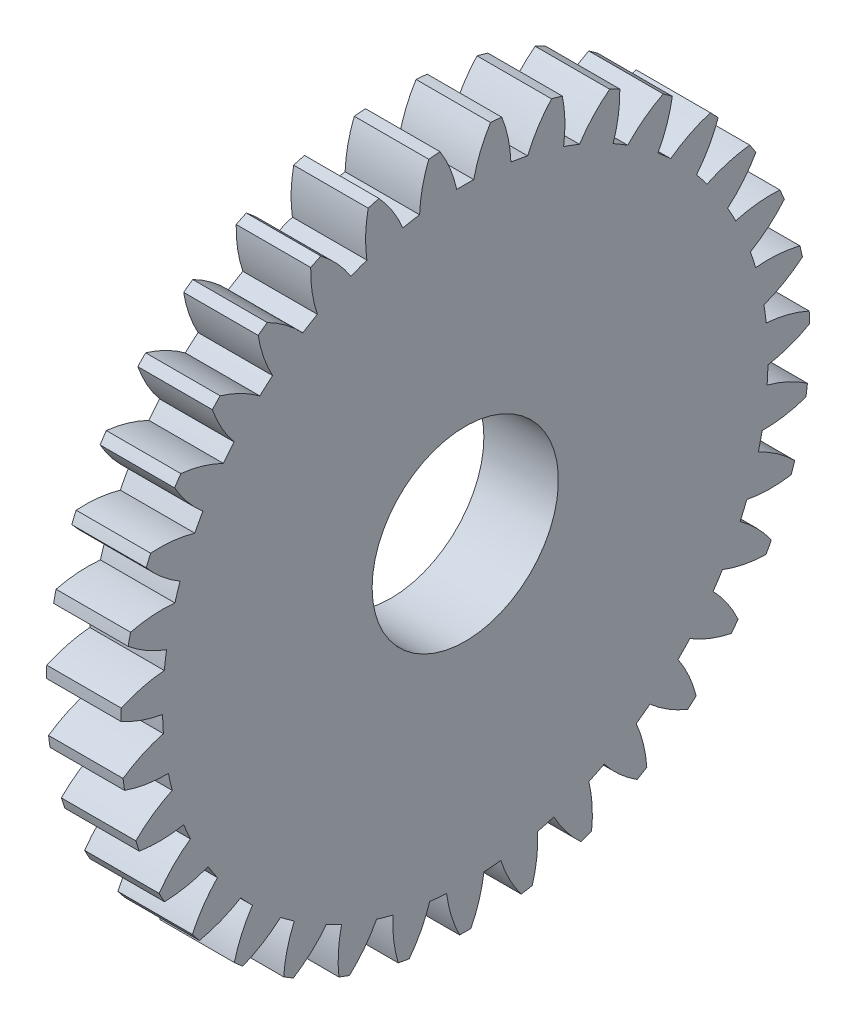
SolidWorks part; units mm, degrees
ref_plane "Plane1" through (0, 0, 0) normal (0, 0, 1) x (1, 0, 0)
ref_plane "Plane2" through (0, 0, 0) normal (0, 1, 0) x (1, 0, 0)
ref_plane "Plane3" through (0, 0, 0) normal (1, 0, 0) x (0, 0, -1)
sketch "HoldingSke" plane through (0, 0, 0) normal (0, 1, 0) x (1, 0, 0)
  line L0 (0, 0) -> (0.8192, -0.5736)
  line L1 (-15, 0) -> (100, 0) construction
  line L2 (0, 0) -> (-2.1039, 2.3779)
  line L3 (0, 0) -> (-11.863, 4.5341)
  line L4 (0, 0) -> (7.0742, 4.9534)
  line L5 (0, 0) -> (-46.8476, -17.4728)
  line L6 (0, 0) -> (-3.3159, -2.2372)
  line L7 (-2.1039, 2.3779) -> (8.6586, 51.2059)
  line L8 (-76.2, 54.61) -> (-74.4, 54.61)
  line L9 (-71.009, 38.7566) -> (-53.1078, 45.2721)
  line L10 (-76.2, 71.12) -> (104.1128, 71.12)
  line L11 (0, 0) -> (-4, 0)
  line L12 (-76.2, 101.6) -> (-76.162, 101.6)
  line L13 (24.9733, 27.94) -> (52.9518, 28.4284)
  line L14 (24.9733, 27.94) -> (24.9743, 27.94)
  line L15 (24.9733, 27.94) -> (100.4006, 29.5858)
  line L16 (-63.627, -1) -> (-12.827, -1)
  circle A0 centre (0, 0) radius 5
  circle A1 centre (0, 0) radius 16.249
  circle A2 centre (0, 0) radius 37.5
  circle A3 centre (0, 0) radius 5
  dimension "MHD" = 32.498
  dimension "Hub_dia" = 75
  dimension "Bore" = 10
  dimension "MBD" = 10
  dimension "Num_teeth" = 35
  dimension "Pitch" = 1
  dimension "Overall_len" = 50
  dimension "Show_teeth" = 35
  dimension "Thickness" = 4
  dimension "OAL" = 50.0001
  dimension "T_dim" = 1.8
  dimension "Ap" = 20
  dimension "H" = 19.05
  dimension "Pitch_radius" = 180.3128
  dimension "Width" = 4
  dimension "Backlash" = 0.038
  dimension "Addendum_fac" = 1
  dimension "Dedendum_fac" = 1.25
  dimension "Clearance_fac" = 0.25
  dimension "Dedendum_add" = 0.001
  dimension "Module" = 1
sketch "BasProSke" plane through (0, 0, 0) normal (0, 1, 0) x (1, 0, 0)
  line L0 (-10, 0) -> (60, 0) construction
  line L1 (0, 0) -> (0, 18.5)
  line L2 (0, 0) -> (4, 0)
  line L3 (4, 0) -> (4, 18.5)
  line L4 (4, 18.5) -> (0, 18.5)
  dimension "Thickness" = 4
  dimension "Diameter" = 37
revolve "Base-Revolve" add sketch "BasProSke" angle 360 about L0
sketch "TooCutSke" plane through (0, 0, 0) normal (1, 0, 0) x (0, 0, -1)
  line L1 (0, 0) -> (0, 107) construction
  line L2 (0, 0) -> (-0.8516, 17.4793) construction
  line L3 (0, 0) -> (-3.1347, 34.8297) construction
  line L4 (-0.8516, 17.4793) -> (-1.5674, 17.4148) construction
  arc A0 (0.4564, 16.2426) -> (-0.4564, 16.2426) centre (0, 0) ccw
  arc A1 (1.373, 18.4745) -> (-1.373, 18.4745) centre (0, 0) ccw
  circle A2 centre (0, 0) radius 17.5 construction
  circle A3 centre (0, 0) radius 16.4446 construction
  arc A4 (-0.4564, 16.2426) -> (-1.373, 18.4745) centre (-7.293, 14.739) ccw
  arc A5 (1.373, 18.4745) -> (0.4564, 16.2426) centre (7.293, 14.739) ccw
  dimension "Root_dia" = 32.498
  dimension "Overcut_dia" = 37.0508
  dimension "Pitch_dia" = 35
  dimension "Base_dia" = 32.8892
  dimension "Flank_rad" = 7
  dimension "Half_ang" = 5.143
  dimension "Half_CT" = 0.7186
extrude "ToothCut" cut sketch "TooCutSke" along normal through all
fillet "Breaks" [suppressed] radius 0.02
fillet "RootFillets" [suppressed] radius 0.251
pattern_circular "TeethCuts" count 35 every 10.286 about axis through (-10, 0, 0) along (1, 0, 0) of "ToothCut", "RootFillets", "Breaks"
sketch "HubNeaOneSke" plane through (0, 0, 0) normal (-1, 0, 0) x (0, 0, 1)
  circle A0 centre (0, 0) radius 16.249
  dimension "Diameter" = 32.498
extrude "HubNearOne" [suppressed] add sketch "HubNeaOneSke" along normal blind 46.0001
sketch "HubNeaBotSke" plane through (0, 0, 0) normal (-1, 0, 0) x (0, 0, 1)
  circle A0 centre (0, 0) radius 16.249
  dimension "Diameter" = 32.498
extrude "HubNearBoth" [suppressed] add sketch "HubNeaBotSke" along normal blind 23
ref_plane "FarPln" through (4, 0, 0) normal (1, 0, 0) x (0, 0, -1)
sketch "HubFarSke" plane through (4, 0, 0) normal (1, 0, 0) x (0, 0, -1)
  circle A0 centre (0, 0) radius 16.249
  dimension "Diameter" = 32.498
extrude "HubFar" [suppressed] add sketch "HubFarSke" along normal blind 23
sketch "BorSke" plane through (0, 0, 0) normal (1, 0, 0) x (0, 0, -1)
  circle A0 centre (0, 0) radius 5
  dimension "Diameter" = 10
extrude "Bore" cut sketch "BorSke" along normal mid plane 100.0001
sketch "KeySke" plane through (0, 0, 0) normal (1, 0, 0) x (0, 0, -1)
  line L0 (-2, 0) -> (-2, 6.8)
  line L1 (-2, 6.8) -> (2, 6.8)
  line L2 (2, 6.8) -> (2, 0)
  line L3 (0, 0) -> (0, 34) construction
  line L4 (-2, 0) -> (2, 0)
  dimension "Width" = 4
  dimension "Offset" = 6.8
extrude "Keyway" [suppressed] cut sketch "KeySke" along normal mid plane 100.0001
pattern_circular "Keyway2" [suppressed] count 2 every 90 about axis through (-10, 0, 0) along (1, 0, 0)
sketch "Sketch1" plane through (4, 0, 0) normal (1, 0, 0) x (0, 0, -1)
  circle A0 centre (0, 0) radius 18.5
equation "' \"Module@HoldingSke\" = 6.35"
equation "' \"Num_teeth@HoldingSke\" = 12"
equation "' \"Ap@HoldingSke\" =  20"
equation "' \"Ap@HoldingSke\" = 20"
equation "' \"Width@HoldingSke\" = 0.5 * 25.4"
equation "' \"Hub_dia@HoldingSke\"= 1 * 25.4"
equation "' \"Hub_dia@HoldingSke\" = 1 * 25.4"
equation "' \"Overall_len@HoldingSke\" = 1.0 * 25.4"
equation "' \"Bore@HoldingSke\" = 0.75 * 25.4"
equation "' \"T_dim@HoldingSke\" = 0.1 * 25.4"
equation "' \"Width@KeySke\" = 0.25 * 25.4"
equation "' \"Show_teeth@HoldingSke\" = 13"
equation "' \"Backlash@HoldingSke\" = 0.009 * 25.4"
equation "' \"Addendum_fac@HoldingSke\" = 1.0"
equation "' \"Dedendum_fac@HoldingSke\" = 1.25"
equation "' \"Dedendum_add@HoldingSke\" = 0.00005 * 25.4"
equation "' \"Clearance_fac@HoldingSke\" = 0.25"
equation "\"Pitch@HoldingSke\" = 1 / \"Module@HoldingSke\""
equation "\"Overcut_dia@TooCutSke\" = (\"Num_teeth@HoldingSke\" + 2 * \"Addendum_fac@HoldingSke\") / \"Pitch@HoldingSke\" + 0.002 * 25.4"
equation "\"Pitch_dia@TooCutSke\" = \"Num_teeth@HoldingSke\" / \"Pitch@HoldingSke\""
equation "\"Base_dia@TooCutSke\" = \"Num_teeth@HoldingSke\" / \"Pitch@HoldingSke\" * cos((\"Ap@HoldingSke\"  * 3.14159265 / 180))"
equation "\"Root_dia@TooCutSke\" = (\"Num_teeth@HoldingSke\" + 2) / \"Pitch@HoldingSke\" - 2 * (\"Addendum_fac@HoldingSke\" + \"Dedendum_fac@HoldingSke\") / \"Pitch@HoldingSke\" - \"Dedendum_add@HoldingSke\" * 2"
equation "\"Half_ang@TooCutSke\" = 180 / \"Num_teeth@HoldingSke\""
equation "\"Half_CT@TooCutSke\" = \"Num_teeth@HoldingSke\" / \"Pitch@HoldingSke\" * sin((3.14159265 / 2 / \"Num_teeth@HoldingSke\")) / 2 - 7 * \"Backlash@HoldingSke\" / 4"
equation "\"Flank_rad@TooCutSke\" = \"Num_teeth@HoldingSke\" / \"Pitch@HoldingSke\" / 5"
equation "\"Radius@RootFillets\" = \"Clearance_fac@HoldingSke\" / \"Pitch@HoldingSke\" + \"Dedendum_add@HoldingSke\""
equation "\"Break_rad@Breaks\" = 0.02 / \"Pitch@HoldingSke\""
equation "\"Thickness@HoldingSke\" = \"Width@HoldingSke\""
equation "\"OAL@HoldingSke\" = \"Thickness@HoldingSke\""
equation "\"MHD@HoldingSke\" = (\"Num_teeth@HoldingSke\" + 2) / \"Pitch@HoldingSke\" - 2 * (\"Addendum_fac@HoldingSke\" + \"Dedendum_fac@HoldingSke\")  / \"Pitch@HoldingSke\" - \"Dedendum_add@HoldingSke\" * 2"
equation "\"MBD@HoldingSke\" = (\"Num_teeth@HoldingSke\" + 2) / \"Pitch@HoldingSke\" - 2 * (\"Addendum_fac@HoldingSke\" + \"Dedendum_fac@HoldingSke\")  / \"Pitch@HoldingSke\" - \"Dedendum_add@HoldingSke\" * 2 - 0.002 * 25.4"
equation "\"MHD@HoldingSke\" = ((sgn( \"MHD@HoldingSke\" - \"Hub_dia@HoldingSke\" )-1)*( \"MHD@HoldingSke\" - \"Hub_dia@HoldingSke\" ))/-2+ \"Hub_dia@HoldingSke\""
equation "\"MBD@HoldingSke\" = ((sgn( \"MBD@HoldingSke\" - \"Bore@HoldingSke\" )-1)*( \"MBD@HoldingSke\" - \"Bore@HoldingSke\" ))/-2+ \"Bore@HoldingSke\""
equation "\"OAL@HoldingSke\" = ((sgn( \"OAL@HoldingSke\" - \"Overall_len@HoldingSke\" )+1)*( \"OAL@HoldingSke\" - \"Overall_len@HoldingSke\" ))/2 + \"Overall_len@HoldingSke\" + 0.000002 * 25.4"
equation "\"Num_teeth@TeethCuts\" = int( \"Show_teeth@HoldingSke\" ) + 1"
equation "\"Num_teeth@TeethCuts\" = ((sgn( \"Num_teeth@TeethCuts\" - \"Num_teeth@HoldingSke\" )-1)*( \"Num_teeth@TeethCuts\" - \"Num_teeth@HoldingSke\" ))/-2+ \"Num_teeth@HoldingSke\""
equation "\"Num_teeth@TeethCuts\" = ((sgn( \"Num_teeth@TeethCuts\" - 2.0)+1)*( \"Num_teeth@TeethCuts\" - 2.0))/2 +2.0"
equation "\"Angle@TeethCuts\" = 360.0 / \"Num_teeth@HoldingSke\""
equation "\"Diameter@BasProSke\" = (\"Num_teeth@HoldingSke\" + 2 * \"Addendum_fac@HoldingSke\") / \"Pitch@HoldingSke\""
equation "\"Thickness@BasProSke\"  = \"Thickness@HoldingSke\""
equation "' \"Fillet_rad@BasProSke\" =  \"Thickness@HoldingSke\" * 0.05"
equation "' \"Fillet_rad@BasProSke\" = \"Thickness@HoldingSke\" * 0.05"
equation "\"MHD@HoldingSke\" = ((sgn( \"MHD@HoldingSke\" - \"Root_dia@TooCutSke\" )-1)*( \"MHD@HoldingSke\" - \"Root_dia@TooCutSke\" ))/-2+ \"Root_dia@TooCutSke\""
equation "\"Diameter@HubNeaOneSke\" = \"MHD@HoldingSke\""
equation "\"Length@HubNearOne\" = \"OAL@HoldingSke\" - \"Thickness@BasProSke\""
equation "\"Diameter@HubNeaBotSke\" = \"MHD@HoldingSke\""
equation "\"Length@HubNearBoth\" = ( \"OAL@HoldingSke\" - \"Thickness@BasProSke\" ) / 2.0"
equation "\"Thickness@FarPln\" = \"Thickness@BasProSke\""
equation "\"Diameter@HubFarSke\" = \"MHD@HoldingSke\""
equation "\"Length@HubFar\" = ( \"OAL@HoldingSke\" - \"Thickness@BasProSke\" ) / 2.0"
equation "\"Diameter@BorSke\" = \"MBD@HoldingSke\""
equation "\"D1@Bore\" = \"OAL@HoldingSke\" * 2.0"
equation "\"D1@Keyway\" = \"OAL@HoldingSke\" * 2.0"
equation "\"Offset@KeySke\" = \"T_dim@HoldingSke\" + \"MBD@HoldingSke\" / 2.0"
